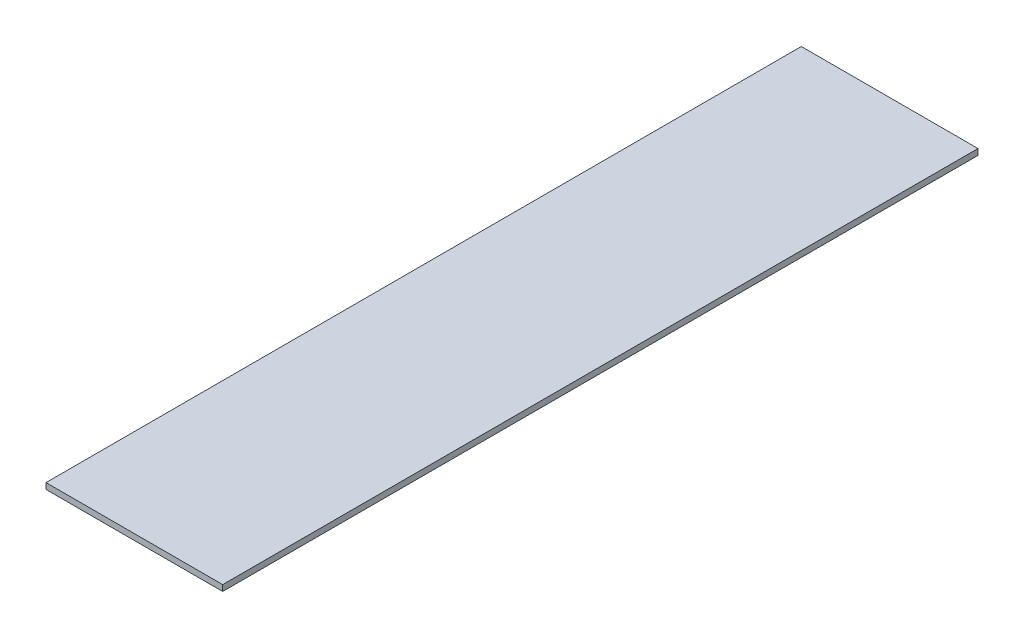
SolidWorks part; units mm, degrees
ref_plane "Front Plane" through (0, 0, 0) normal (0, 0, 1) x (1, 0, 0)
ref_plane "Top Plane" through (0, 0, 0) normal (0, 1, 0) x (1, 0, 0)
ref_plane "Right Plane" through (0, 0, 0) normal (1, 0, 0) x (0, 0, -1)
sketch "Sketch2" plane through (0, 0, 0) normal (0, 1, 0) x (1, 0, 0)
  line L1 (-66.55, 284.5) -> (66.55, 284.5)
  line L2 (-66.55, 284.5) -> (-66.55, -284.5)
  line L3 (-66.55, -284.5) -> (66.55, -284.5)
  line L4 (66.55, 284.5) -> (66.55, -284.5)
  dimension "D1" = 133.1
  dimension "D2" = 66.55
  dimension "D3" = 569
  dimension "D4" = 284.5
extrude "Boss-Extrude1" add sketch "Sketch2" along normal blind 4.5
